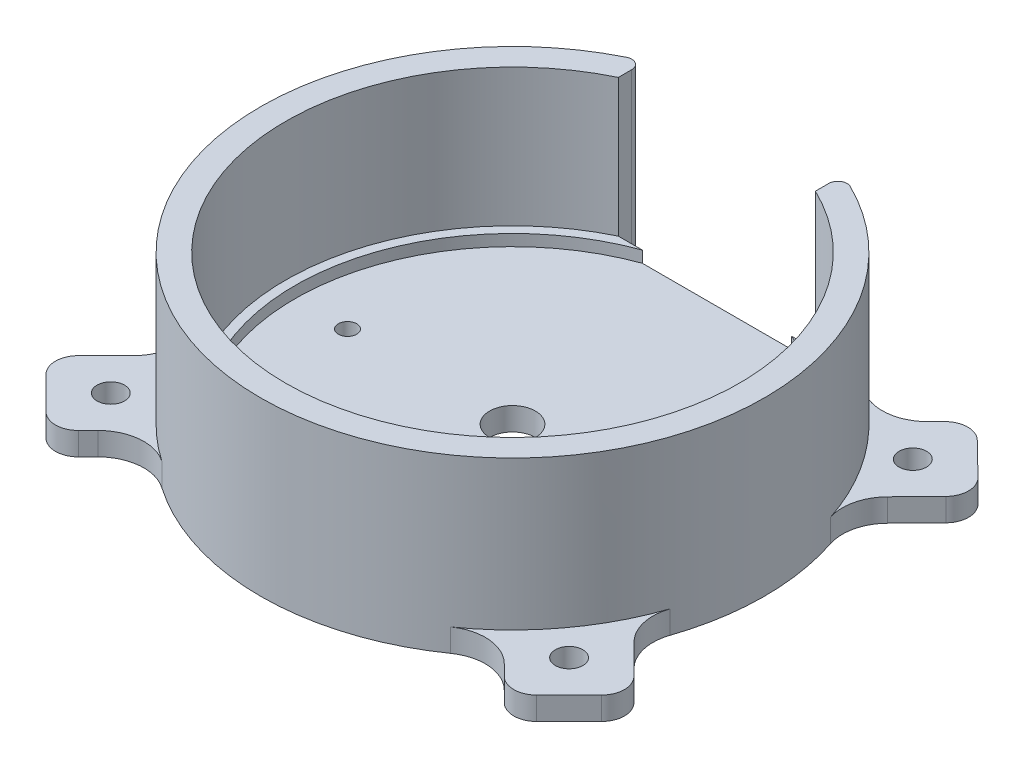
SolidWorks part; units mm, degrees
ref_plane "前视基准面" through (0, 0, 0) normal (0, 0, 1) x (1, 0, 0)
ref_plane "上视基准面" through (0, 0, 0) normal (0, 1, 0) x (1, 0, 0)
ref_plane "右视基准面" through (0, 0, 0) normal (1, 0, 0) x (0, 0, -1)
other "Configuration Table"
sketch "草图1" plane through (0, 0, 0) normal (0, 1, 0) x (1, 0, 0)
  circle A0 centre (0, 0) radius 55
  dimension "D1" = 110
extrude "凸台-拉伸1" add sketch "草图1" along normal blind 37.5
sketch "草图3" plane through (0, 37.5, 0) normal (0, 1, 0) x (1, 0, 0)
  circle A0 centre (0, 0) radius 49.5
  dimension "D1" = 99
extrude "切除-拉伸1" cut sketch "草图3" against normal blind 32.5
sketch "草图5" plane through (0, 37.5, 0) normal (0, 1, 0) x (1, 0, 0)
  line L0 (0, 0) -> (0, 49.5) construction
  line L1 (-21.5, 44.587) -> (21.5, 44.587)
  line L2 (-21.5, 44.587) -> (-21.5, 56.8299)
  line L3 (-21.5, 56.8299) -> (21.5, 56.8299)
  line L4 (21.5, 56.8299) -> (21.5, 44.587)
  circle A0 centre (0, 0) radius 49.5 construction
  circle A1 centre (0, 0) radius 49.5 construction
  dimension "D1" = 43
extrude "切除-拉伸2" cut sketch "草图5" against normal blind 40
fillet "圆角4" radius 2 1 edges at (-21.5, 18.75, -50.6236)
fillet "圆角5" radius 2 1 edges at (21.5, 18.75, -50.6236)
sketch "草图6" plane through (0, 5, 0) normal (0, 1, 0) x (1, 0, 0)
  circle A0 centre (0, 0) radius 5
  dimension "D1" = 10
extrude "切除-拉伸3" cut sketch "草图6" against normal blind 12 contours A0
sketch "草图10" plane through (0, 5, 0) normal (0, 1, 0) x (1, 0, 0)
  line L0 (-49.7204, 37.0712) -> (62.5452, 37.0712) construction
  line L1 (-49.7204, 37.0712) -> (-49.7204, -35.3765) construction
  line L2 (-49.7204, -37.9288) -> (73.1761, -37.9288) construction
  circle A0 centre (-49.7204, 37.0712) radius 3
  circle A1 centre (50.2796, 37.0712) radius 3
  circle A2 centre (-49.7204, -37.9288) radius 3
  circle A3 centre (50.2796, -37.9288) radius 3
  dimension "D1" = 6
  dimension "D2" = 6
  dimension "D4" = 6
  dimension "D6" = 6
  dimension "D3" = 100
  dimension "D5" = 75
  dimension "D7" = 100
sketch "草图14" plane through (0, 5, 0) normal (0, 1, 0) x (1, 0, 0)
  line L0 (-49.8986, 23.1329) -> (-63.8625, 37.0448)
  line L1 (-63.8625, 37.0448) -> (-49.7468, 51.2133)
  line L2 (-49.7468, 51.2133) -> (-38.1286, 39.6385)
  line L3 (49.8119, -23.319) -> (64.4217, -37.9288)
  line L4 (-49.6324, -23.6986) -> (-63.8626, -37.9288)
  line L5 (-63.8626, -37.9288) -> (-49.7204, -52.0709)
  line L6 (-49.7204, -52.0709) -> (-37.6979, -40.0484)
  line L7 (38.4757, 39.3016) -> (50.1189, 51.2124)
  line L8 (50.1189, 51.2124) -> (64.4208, 37.2319)
  line L9 (64.4208, 37.2319) -> (50.1345, 22.6171)
  line L10 (64.4217, -37.9288) -> (50.2796, -52.0709)
  line L11 (50.2796, -52.0709) -> (37.9849, -39.7762)
  arc A0 (-24.3868, 49.2979) -> (24.3868, 49.2979) centre (0, 0) ccw construction
  arc A1 (-49.6324, -23.6986) -> (-37.6979, -40.0484) centre (0, 0) ccw
  arc A2 (-49.8986, 23.1329) -> (-38.1286, 39.6385) centre (0, 0) cw
  arc A3 (38.4757, 39.3016) -> (50.1345, 22.6171) centre (0, 0) cw
  arc A4 (49.8119, -23.319) -> (37.9849, -39.7762) centre (0, 0) cw
  dimension "D1" = 10
  dimension "D2" = 10
  dimension "D3" = 10
  dimension "D4" = 10
  dimension "D5" = 10
  dimension "D6" = 10
  dimension "D7" = 10
  dimension "D8" = 10
  dimension "D9" = 10
  dimension "D10" = 10
  dimension "D11" = 10
  dimension "D12" = 10
extrude "凸台-拉伸3" add sketch "草图14" against normal up to surface (5 mm away) up to face at (0, 0, 5)
fillet "圆角7" radius 10 8 edges at (-49.6324, 2.5, 23.6986) (-37.6979, 2.5, 40.0484) (37.9849, 2.5, 39.7762) (49.8119, 2.5, 23.319) (50.1345, 2.5, -22.6171) (38.4757, 2.5, -39.3016) (-38.1286, 2.5, -39.6385) (-49.8986, 2.5, -23.1329)
fillet "圆角8" radius 5 8 edges at (-49.7468, 2.5, -51.2133) (-63.8625, 2.5, -37.0448) (-63.8626, 2.5, 37.9288) (-49.7204, 2.5, 52.0709) (50.2796, 2.5, 52.0709) (64.4217, 2.5, 37.9288) (64.4208, 2.5, -37.2319) (50.1189, 2.5, -51.2124)
extrude "切除-拉伸5" cut sketch "草图10" against normal up to surface (5 mm away) up to face at (0, 0, 5)
sketch "草图15" plane through (0, 5, 0) normal (0, 1, 0) x (1, 0, 0)
  line L0 (-21.5, 44.587) -> (21.5, 44.587) construction
  line L1 (-21.5, 44.587) -> (-16.2558, 44.587)
  line L2 (16.2558, 44.587) -> (21.5, 44.587)
  arc A0 (-21.5, 44.587) -> (21.5, 44.587) centre (0, 0) ccw
  arc A1 (-16.2558, 44.587) -> (16.2558, 44.587) centre (0, 0) ccw
extrude "凸台-拉伸4" add sketch "草图15" along normal blind 2.5
sketch "草图16" plane through (0, 0, 0) normal (0, -1, 0) x (-1, 0, 0)
  line L0 (0, 0) -> (33.9878, 0) construction
  circle A0 centre (36, 0) radius 2
  circle A1 centre (-36, 0) radius 2
  dimension "D3" = 4
  dimension "D4" = 4
  dimension "D1" = 72
  dimension "D2" = 36
extrude "切除-拉伸6" cut sketch "草图16" against normal blind 10
